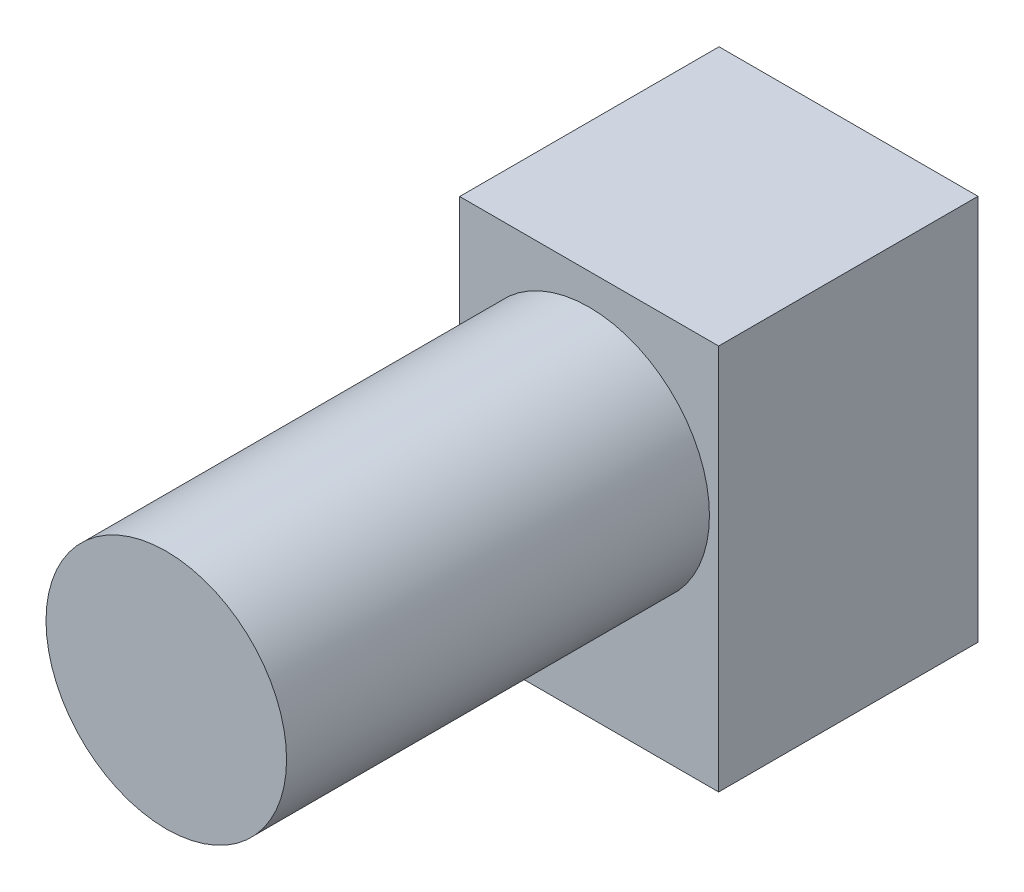
SolidWorks part; units mm, degrees
ref_plane "Front Plane" through (0, 0, 0) normal (0, 0, 1) x (1, 0, 0)
ref_plane "Top Plane" through (0, 0, 0) normal (0, 1, 0) x (1, 0, 0)
ref_plane "Right Plane" through (0, 0, 0) normal (1, 0, 0) x (0, 0, -1)
sketch "Sketch1" plane through (0, 0, 0) normal (0, 0, 1) x (1, 0, 0)
  line L1 (-3.5, -5.22) -> (3.5, -5.22)
  line L2 (-3.5, -5.22) -> (-3.5, 5.22)
  line L3 (-3.5, 5.22) -> (3.5, 5.22)
  line L4 (3.5, -5.22) -> (3.5, 5.22)
  line L5 (-3.5, -5.22) -> (3.5, 5.22) construction
  line L6 (-3.5, 5.22) -> (3.5, -5.22) construction
  point P0 (0, 0)
  dimension "D1" = 7
  dimension "D2" = 10.44
extrude "Extrude1" add sketch "Sketch1" along normal blind 7.0104
sketch "Sketch2" plane through (0, 0, 7.0104) normal (0, 0, 1) x (1, 0, 0)
  line L0 (0, -5.22) -> (0, 1.13) construction
  line L1 (-3.5, -5.22) -> (3.5, -5.22) construction
  circle A0 centre (0, 1.13) radius 3.2512
  dimension "D2" = 6.5024
  dimension "D1" = 6.35
extrude "Extrude2" add sketch "Sketch2" along normal blind 11.43
